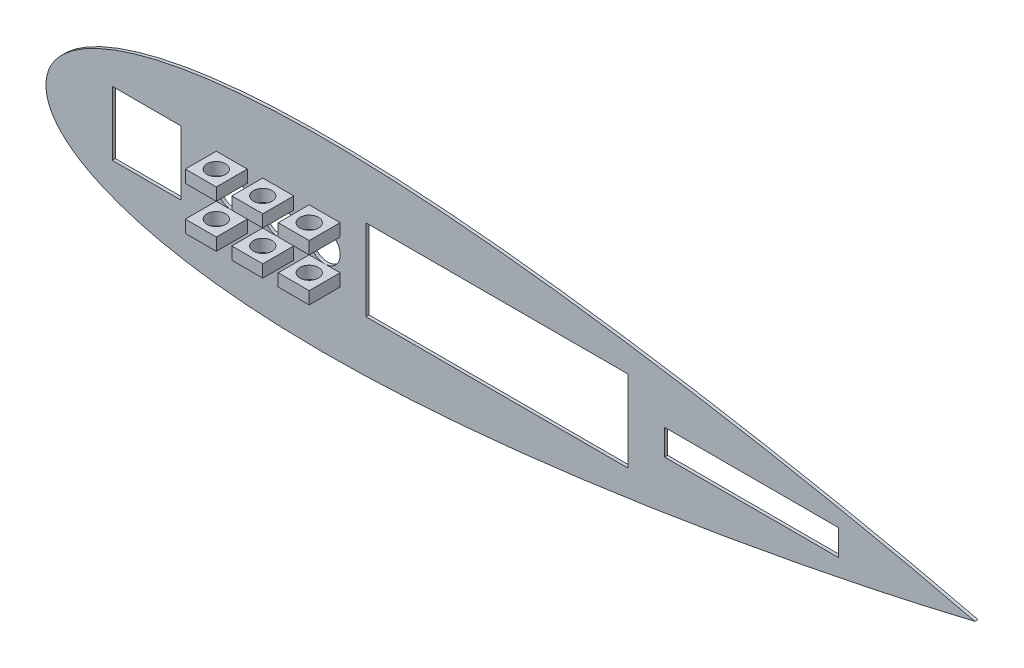
SolidWorks part; units mm, degrees
ref_plane "前视基准面" through (0, 0, 0) normal (0, 0, 1) x (1, 0, 0)
ref_plane "上视基准面" through (0, 0, 0) normal (0, 1, 0) x (1, 0, 0)
ref_plane "右视基准面" through (0, 0, 0) normal (1, 0, 0) x (0, 0, -1)
sketch "草图1" plane through (0, 0, 0) normal (0, 0, 1) x (1, 0, 0)
  spline S0 degree 4 poles (0, 0) (-0.0002, 0.507) (0.0449, 1.3817) (0.226, 2.6508) (0.688, 4.3) (1.3355, 5.873) (2.267, 7.5426) (3.5719, 9.3461) (5.3914, 11.3247) (7.9545, 13.5395) (11.585, 16.0215) (16.6481, 18.727) (23.7932, 21.6498) (33.0858, 24.4369) (46.6431, 27.2845) (64.0632, 29.3627) (84.4508, 30.2603) (107.4149, 29.86) (130.3326, 28.4283) (153.1861, 26.2148) (175.9708, 23.3917) (195.8486, 20.4876) (212.8449, 17.733) (226.9805, 15.2709) (238.2713, 13.2039) (248.1352, 11.3101) (256.5773, 9.6255) (263.6047, 8.1795) (269.2198, 6.9974) (274.131, 5.9394) (278.332, 5.0171) (281.8385, 4.235) (284.6266, 3.6061) (287.4466, 2.9621) (290.2003, 2.3266) (293.0761, 1.6538) (295.7002, 1.0342) (299.1487, 0.2076) (301.6998, -0.4115) (305.9289, -1.45) (309.2336, -2.281) (313.2598, -3.3026) (316.8434, -4.2332) (320.6976, -5.2459) (323.9028, -6.1065) (326.7456, -6.8783) (328.5968, -7.3881) (329.5319, -7.6468) (330.0005, -7.7768) knots 0 0 0 0 0 0.005875 0.010168 0.014828 0.019835 0.025575 0.032309 0.04061 0.050967 0.064812 0.083253 0.107121 0.14043 0.177264 0.243882 0.3105 0.377118 0.443736 0.510354 0.576972 0.64359 0.676899 0.710208 0.743517 0.776826 0.793481 0.810135 0.82679 0.843444 0.851772 0.860099 0.868426 0.876753 0.885081 0.893408 0.901735 0.910062 0.921305 0.932547 0.943789 0.955031 0.966273 0.977516 0.988758 0.994379 1 1 1 1 1 construction
  spline S1 degree 4 poles (0, 0) (-0.0002, 0.507) (0.0449, 1.3817) (0.226, 2.6508) (0.688, 4.3) (1.3355, 5.873) (2.267, 7.5426) (3.5719, 9.3461) (5.3914, 11.3247) (7.9545, 13.5395) (11.585, 16.0215) (16.6481, 18.727) (23.7932, 21.6498) (33.0858, 24.4369) (46.6431, 27.2845) (64.0632, 29.3627) (84.4508, 30.2603) (107.4149, 29.86) (130.3326, 28.4283) (153.1861, 26.2148) (175.9708, 23.3917) (195.8486, 20.4876) (212.8449, 17.733) (226.9805, 15.2709) (238.2713, 13.2039) (248.1352, 11.3101) (256.5773, 9.6255) (263.6047, 8.1795) (269.2198, 6.9974) (274.131, 5.9394) (278.332, 5.0171) (281.8385, 4.235) (284.6266, 3.6061) (287.4466, 2.9621) (290.2003, 2.3266) (293.0761, 1.6538) (295.7002, 1.0342) (298.0785, 0.4641) (299.3655, 0.1537) (300, 0) knots 0 0 0 0 0 0.005875 0.010168 0.014828 0.019835 0.025575 0.032309 0.04061 0.050967 0.064812 0.083253 0.107121 0.14043 0.177264 0.243882 0.3105 0.377118 0.443736 0.510354 0.576972 0.64359 0.676899 0.710208 0.743517 0.776826 0.793481 0.810135 0.82679 0.843444 0.851772 0.860099 0.868426 0.876753 0.885081 0.893408 0.901735 0.910062 0.910062 0.910062 0.910062 0.910062
  spline S2 degree 4 poles (0, 0) (-0.0002, -0.507) (0.0449, -1.3817) (0.226, -2.6508) (0.688, -4.3) (1.3355, -5.873) (2.267, -7.5426) (3.5719, -9.3461) (5.3914, -11.3247) (7.9545, -13.5395) (11.585, -16.0215) (16.6481, -18.727) (23.7932, -21.6498) (33.0858, -24.4369) (46.6431, -27.2845) (64.0632, -29.3627) (84.4508, -30.2603) (107.4149, -29.86) (130.3326, -28.4283) (153.1861, -26.2148) (175.9708, -23.3917) (195.8486, -20.4876) (212.8449, -17.733) (226.9805, -15.2709) (238.2713, -13.2039) (248.1352, -11.3101) (256.5773, -9.6255) (263.6047, -8.1795) (269.2198, -6.9974) (274.131, -5.9394) (278.332, -5.0171) (281.8385, -4.235) (284.6266, -3.6061) (287.4466, -2.9621) (290.2003, -2.3266) (293.0761, -1.6538) (295.7002, -1.0342) (299.1487, -0.2076) (301.6998, 0.4115) (305.9289, 1.45) (309.2336, 2.281) (313.2598, 3.3026) (316.8434, 4.2332) (320.6976, 5.2459) (323.9028, 6.1065) (326.7456, 6.8783) (328.5968, 7.3881) (329.5319, 7.6468) (330.0005, 7.7768) knots 0 0 0 0 0 0.005875 0.010168 0.014828 0.019835 0.025575 0.032309 0.04061 0.050967 0.064812 0.083253 0.107121 0.14043 0.177264 0.243882 0.3105 0.377118 0.443736 0.510354 0.576972 0.64359 0.676899 0.710208 0.743517 0.776826 0.793481 0.810135 0.82679 0.843444 0.851772 0.860099 0.868426 0.876753 0.885081 0.893408 0.901735 0.910062 0.921305 0.932547 0.943789 0.955031 0.966273 0.977516 0.988758 0.994379 1 1 1 1 1 construction
  spline S3 degree 4 poles (0, 0) (-0.0002, -0.507) (0.0449, -1.3817) (0.226, -2.6508) (0.688, -4.3) (1.3355, -5.873) (2.267, -7.5426) (3.5719, -9.3461) (5.3914, -11.3247) (7.9545, -13.5395) (11.585, -16.0215) (16.6481, -18.727) (23.7932, -21.6498) (33.0858, -24.4369) (46.6431, -27.2845) (64.0632, -29.3627) (84.4508, -30.2603) (107.4149, -29.86) (130.3326, -28.4283) (153.1861, -26.2148) (175.9708, -23.3917) (195.8486, -20.4876) (212.8449, -17.733) (226.9805, -15.2709) (238.2713, -13.2039) (248.1352, -11.3101) (256.5773, -9.6255) (263.6047, -8.1795) (269.2198, -6.9974) (274.131, -5.9394) (278.332, -5.0171) (281.8385, -4.235) (284.6266, -3.6061) (287.4466, -2.9621) (290.2003, -2.3266) (293.0761, -1.6538) (295.7002, -1.0342) (298.0785, -0.4641) (299.3655, -0.1537) (300, 0) knots 0 0 0 0 0 0.005875 0.010168 0.014828 0.019835 0.025575 0.032309 0.04061 0.050967 0.064812 0.083253 0.107121 0.14043 0.177264 0.243882 0.3105 0.377118 0.443736 0.510354 0.576972 0.64359 0.676899 0.710208 0.743517 0.776826 0.793481 0.810135 0.82679 0.843444 0.851772 0.860099 0.868426 0.876753 0.885081 0.893408 0.901735 0.910062 0.910062 0.910062 0.910062 0.910062
  point P0 (-34.8223, 16.4371)
extrude "凸台-拉伸1" add sketch "草图1" along normal blind 1
sketch "草图2" plane through (0, 0, 1) normal (0, 0, 1) x (1, 0, 0)
  circle A0 centre (60, 0) radius 5
  circle A1 centre (75, 0) radius 5
  circle A2 centre (90, 0) radius 5
  point P36 (0, 0)
  point P38 (0, 0)
  point P39 (0, 0)
  point P40 (0, 0)
  point P41 (0, 0)
  point P42 (0, 0)
  point P43 (73.3219, -13.5821)
  point P44 (103.3497, -11.6877)
  point P45 (84.3936, -15.3435)
extrude "切除-拉伸2" cut sketch "草图2" against normal through all
sketch "草图7" plane through (0, 0, 1) normal (0, 0, 1) x (1, 0, 0)
  line L1 (55, 9) -> (65, 9)
  line L2 (55, 9) -> (55, 5)
  line L3 (55, 5) -> (65, 5)
  line L4 (65, 9) -> (65, 5)
  line L5 (55, 9) -> (65, 5) construction
  line L6 (55, 5) -> (65, 9) construction
  line L7 (55, -5) -> (65, -5)
  line L8 (55, -5) -> (55, -9)
  line L9 (55, -9) -> (65, -9)
  line L10 (65, -5) -> (65, -9)
  line L11 (55, -5) -> (65, -9) construction
  line L12 (55, -9) -> (65, -5) construction
  line L13 (70, 9) -> (80, 9)
  line L14 (70, 9) -> (70, 5)
  line L15 (70, 5) -> (80, 5)
  line L16 (80, 9) -> (80, 5)
  line L17 (70, 9) -> (80, 5) construction
  line L18 (70, 5) -> (80, 9) construction
  line L19 (70, -5) -> (80, -5)
  line L20 (70, -5) -> (70, -9)
  line L21 (70, -9) -> (80, -9)
  line L22 (80, -5) -> (80, -9)
  line L23 (70, -5) -> (80, -9) construction
  line L24 (70, -9) -> (80, -5) construction
  line L25 (85, 9) -> (95, 9)
  line L26 (85, 9) -> (85, 5)
  line L27 (85, 5) -> (95, 5)
  line L28 (95, 9) -> (95, 5)
  line L29 (85, 9) -> (95, 5) construction
  line L30 (85, 5) -> (95, 9) construction
  line L31 (85, -5) -> (95, -5)
  line L32 (85, -5) -> (85, -9)
  line L33 (85, -9) -> (95, -9)
  line L34 (95, -5) -> (95, -9)
  line L35 (85, -5) -> (95, -9) construction
  line L36 (85, -9) -> (95, -5) construction
  point P0 (60, 7)
  point P5 (60, -7)
  point P10 (75, 7)
  point P15 (75, -7)
  point P20 (90, 7)
  point P25 (90, -7)
extrude "凸台-拉伸2" add sketch "草图7" along normal blind 10
sketch "草图8" plane through (0, -9, 0) normal (0, -1, 0) x (1, 0, 0)
  circle A0 centre (90, 6) radius 3
  circle A1 centre (75, 6) radius 3
  circle A2 centre (60, 6) radius 3
  point P6 (0, 0)
  point P7 (0, 0)
  point P8 (0, 0)
  point P9 (0, 0)
extrude "切除-拉伸3" cut sketch "草图8" against normal through all both and the other way through all
sketch "草图9" plane through (0, 0, 1) normal (0, 0, 1) x (1, 0, 0)
  line L1 (103.3265, 13.1366) -> (188.0186, 13.1366)
  line L2 (103.3265, 13.1366) -> (103.3265, -13.1366)
  line L3 (103.3265, -13.1366) -> (188.0186, -13.1366)
  line L4 (188.0186, 13.1366) -> (188.0186, -13.1366)
  line L5 (103.3265, 13.1366) -> (188.0186, -13.1366) construction
  line L6 (103.3265, -13.1366) -> (188.0186, 13.1366) construction
  line L7 (199.7643, 4.1728) -> (256.0197, 4.1728)
  line L8 (199.7643, 4.1728) -> (199.7643, -4.1728)
  line L9 (199.7643, -4.1728) -> (256.0197, -4.1728)
  line L10 (256.0197, 4.1728) -> (256.0197, -4.1728)
  line L11 (199.7643, 4.1728) -> (256.0197, -4.1728) construction
  line L12 (199.7643, -4.1728) -> (256.0197, 4.1728) construction
  line L13 (21.4162, 10.3547) -> (43.671, 10.3547)
  line L14 (21.4162, 10.3547) -> (21.4162, -10.3547)
  line L15 (21.4162, -10.3547) -> (43.671, -10.3547)
  line L16 (43.671, 10.3547) -> (43.671, -10.3547)
  line L17 (21.4162, 10.3547) -> (43.671, -10.3547) construction
  line L18 (21.4162, -10.3547) -> (43.671, 10.3547) construction
  point P0 (145.6726, 0)
  point P5 (227.892, 0)
  point P10 (32.5436, 0)
extrude "切除-拉伸4" cut sketch "草图9" against normal through all
